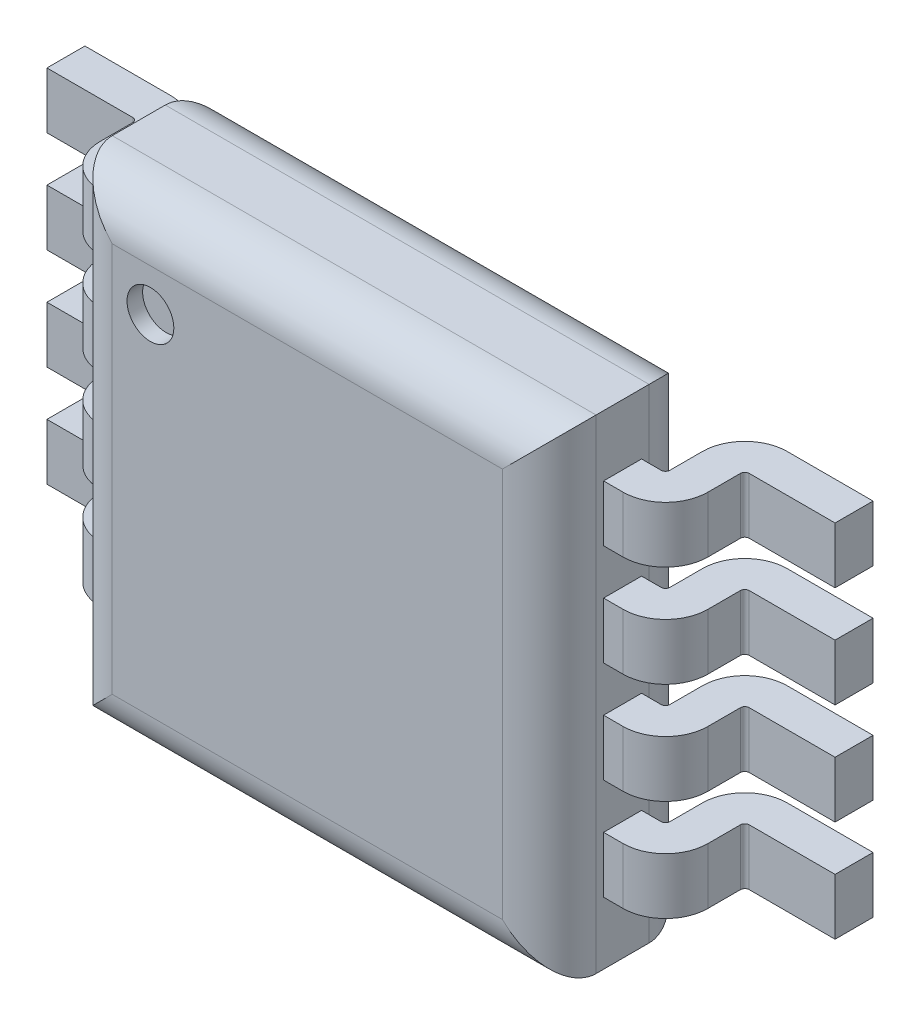
SolidWorks part; units mm, degrees
ref_plane "Спереди" through (0, 0, 0) normal (0, 0, 1) x (1, 0, 0)
ref_plane "Сверху" through (0, 0, 0) normal (0, 1, 0) x (1, 0, 0)
ref_plane "Справа" through (0, 0, 0) normal (1, 0, 0) x (0, 0, -1)
ref_plane "Плоскость1" through (0, 0, 1.1) normal (0, 0, 1) x (1, 0, 0)
sketch "Эскиз3" plane through (0, 0, 1.1) normal (0, 0, 1) x (1, 0, 0)
  line L1 (0.625, 0.57) -> (3.725, 0.57)
  line L2 (0.625, 0.57) -> (0.625, -2.53)
  line L3 (0.625, -2.53) -> (3.725, -2.53)
  line L4 (3.725, 0.57) -> (3.725, -2.53)
  dimension "D1" = 3.1
  dimension "D2" = 3.1
extrude "Вытянуть1" add sketch "Эскиз3" against normal blind 0.94
fillet "Скругление2" radius 0.3
sketch "Эскиз4" plane through (0, 0, 1.1) normal (0, 0, 1) x (1, 0, 0)
  circle A0 centre (1.1697, 0) radius 0.15
extrude "Вырез-Вытянуть1" cut sketch "Эскиз4" against normal blind 0.1
ref_plane "Плоскость2" through (-0.35, 0, 0) normal (1, 0, 0) x (0, 0, -1)
sketch "Эскиз5" plane through (-0.35, 0, 0) normal (1, 0, 0) x (0, 0, -1)
  line L0 (0, -0.47) -> (-0.2434, -0.47)
  line L1 (0, 0.18) -> (-0.2434, 0.18)
  line L2 (0, 0.18) -> (0, -0.18)
  line L3 (0, -0.18) -> (-0.2434, -0.18)
  line L4 (-0.2434, 0.18) -> (-0.2434, -0.18)
  line L5 (0, -0.47) -> (0, -0.83)
  line L6 (0, -0.83) -> (-0.2434, -0.83)
  line L7 (-0.2434, -0.47) -> (-0.2434, -0.83)
  line L8 (0, -1.12) -> (-0.2434, -1.12)
  line L9 (0, -1.12) -> (0, -1.48)
  line L10 (0, -1.48) -> (-0.2434, -1.48)
  line L11 (-0.2434, -1.12) -> (-0.2434, -1.48)
  line L12 (0, -1.77) -> (-0.2434, -1.77)
  line L13 (0, -1.77) -> (0, -2.13)
  line L14 (0, -2.13) -> (-0.2434, -2.13)
  line L15 (-0.2434, -1.77) -> (-0.2434, -2.13)
sketch "Эскиз6" plane through (0, 0, 0) normal (0, 1, 0) x (1, 0, 0)
  line L0 (0.625, -0.63) -> (0.5, -0.63)
  line L2 (0.625, -0.46) -> (0.625, -0.8) construction
  line L3 (0.35, -0.48) -> (0.35, -0.2717)
  line L4 (0.2, -0.1217) -> (-0.35, -0.1217)
  line L5 (-0.35, 0) -> (-0.35, -0.2434) construction
  line L6 (2.175, -0.46) -> (2.175, -0.8) construction
  line L7 (3.725, -0.46) -> (0.625, -0.46) construction
  line L8 (0.625, -0.8) -> (3.725, -0.8) construction
  line L9 (4.15, -0.1217) -> (4.7, -0.1217)
  line L10 (4, -0.48) -> (4, -0.2717)
  line L11 (3.725, -0.63) -> (3.85, -0.63)
  line L12 (0.625, -0.63) -> (3.725, -0.63)
  arc A0 (0.5, -0.63) -> (0.35, -0.48) centre (0.5, -0.48) cw
  arc A1 (0.35, -0.2717) -> (0.2, -0.1217) centre (0.2, -0.2717) ccw
  arc A2 (4, -0.2717) -> (4.15, -0.1217) centre (4.15, -0.2717) cw
  arc A3 (3.85, -0.63) -> (4, -0.48) centre (3.85, -0.48) ccw
  dimension "D2" = 0.15
  dimension "D1" = 0.7
sweep "По траектории4" add profiles "Эскиз5" path "Эскиз6"
